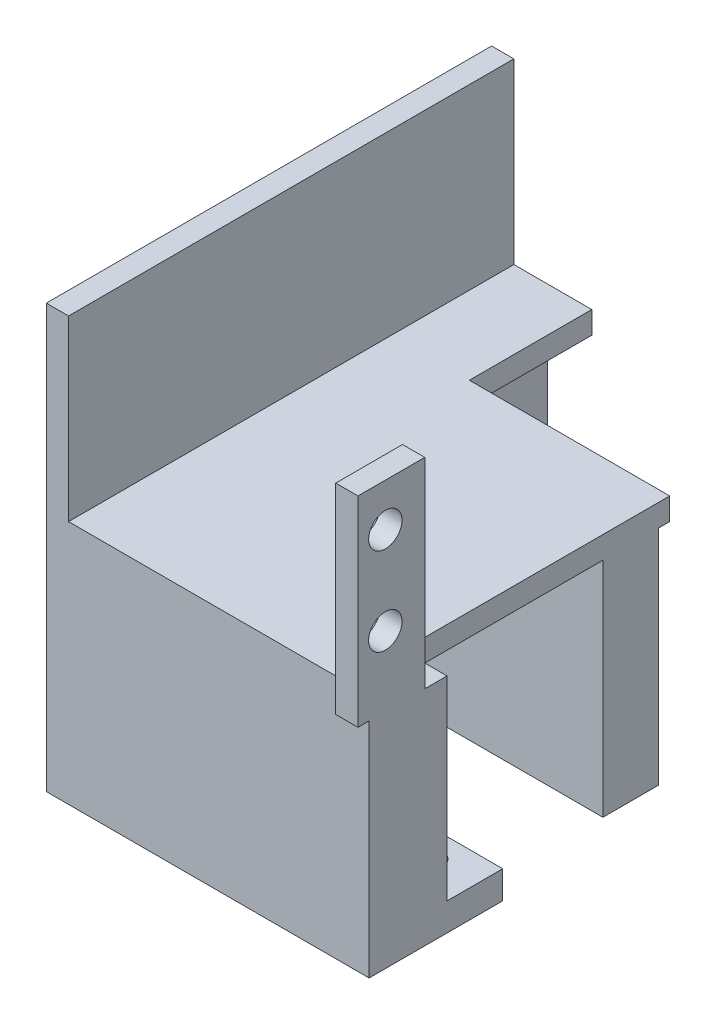
SolidWorks part; units mm, degrees
material "ABS"
ref_plane "Front" through (0, 0, 0) normal (0, 0, 1) x (1, 0, 0)
ref_plane "Top" through (0, 0, 0) normal (0, 1, 0) x (1, 0, 0)
ref_plane "Right" through (0, 0, 0) normal (1, 0, 0) x (0, 0, -1)
sketch "Sketch1" plane through (0, 0, 0) normal (0, 1, 0) x (1, 0, 0)
  line L1 (0, 0) -> (31.75, 0)
  line L2 (0, 0) -> (0, 54.61)
  line L3 (0, 54.61) -> (31.75, 54.61)
  line L4 (31.75, 0) -> (31.75, 54.61)
  dimension "D1" = 31.75
  dimension "D2" = 54.61
extrude "Boss-Extrude1" add sketch "Sketch1" along normal blind 2.54 contours L1 L4 L3 L2
sketch "Sketch2" plane through (0, 0, 0) normal (0, 1, 0) x (1, 0, 0)
  line L0 (31.75, 27.305) -> (-11.8437, 27.305) construction
  line L1 (31.75, -1.27) -> (34.29, -1.27)
  line L2 (31.75, -1.27) -> (31.75, 6.35)
  line L3 (31.75, 6.35) -> (34.29, 6.35)
  line L4 (34.29, -1.27) -> (34.29, 6.35)
  line L6 (31.75, 0) -> (31.75, 54.61) construction
  line L7 (31.75, 48.26) -> (34.29, 48.26)
  line L8 (34.29, 55.88) -> (34.29, 48.26)
  line L9 (31.75, 55.88) -> (34.29, 55.88)
  line L10 (31.75, 55.88) -> (31.75, 48.26)
  line L11 (0, 0) -> (31.75, 0) construction
  line L12 (0, 0) -> (-2.54, 0)
  line L13 (0, 0) -> (0, 54.61)
  line L14 (0, 54.61) -> (-2.54, 54.61)
  line L15 (-2.54, 0) -> (-2.54, 54.61)
  point P8 (31.75, 27.305)
  dimension "D1" = 7.62
  dimension "D2" = 2.54
  dimension "D3" = 2.54
  dimension "D4" = 1.27
extrude "Boss-Extrude2" add sketch "Sketch2" along normal blind 22.86
sketch "Sketch3" plane through (0, 0, 0) normal (0, -1, 0) x (1, 0, 0)
  line L0 (34.29, 1.27) -> (34.29, -6.35) construction
  line L1 (-2.54, 0) -> (34.29, 0)
  line L2 (-2.54, 0) -> (-2.54, -8.89)
  line L3 (-2.54, -8.89) -> (34.29, -8.89)
  line L4 (34.29, 0) -> (34.29, -8.89)
  line L5 (-2.54, -27.305) -> (39.9335, -27.305) construction
  line L8 (31.75, -6.35) -> (31.75, -48.26) construction
  line L9 (-2.54, -45.72) -> (34.29, -45.72)
  line L10 (34.29, -54.61) -> (34.29, -45.72)
  line L11 (-2.54, -54.61) -> (34.29, -54.61)
  line L12 (-2.54, -54.61) -> (-2.54, -45.72)
  point P10 (31.75, -27.305)
  dimension "D1" = 8.89
extrude "Boss-Extrude3" add sketch "Sketch3" along normal blind 25.4
sketch "Sketch4" plane through (34.29, 0, 0) normal (1, 0, 0) x (0, 0, -1)
  line L1 (27.305, -7.6729) -> (27.305, 45.0882) construction
  line L2 (6.35, 2.54) -> (48.26, 2.54) construction
  circle A0 centre (1.85, 17.9678) radius 1.905
  circle A1 centre (1.85, 7.9678) radius 1.905
  circle A2 centre (52.76, 17.9678) radius 1.905
  circle A3 centre (52.76, 7.9678) radius 1.905
  arc A4 (-0.1731, 16.2178) -> (-0.1731, 19.7178) centre (1.85, 17.9678) ccw construction
  arc A5 (0.205, 6.5449) -> (0.205, 9.3907) centre (1.85, 7.9678) ccw construction
  point P11 (27.305, 2.54)
  dimension "D1" = 3.81
  dimension "D2" = 3.81
extrude "Cut-Extrude1" cut sketch "Sketch4" against normal up to surface (2.54 mm away) up to face at (31.75, 8.4667, -52.9167)
sketch "Sketch5" plane through (0, 0, -54.61) normal (0, 0, -1) x (-1, 0, 0)
  line L1 (-34.29, 0) -> (2.54, 0)
  line L2 (-34.29, 0) -> (-34.29, -25.4)
  line L3 (-34.29, -25.4) -> (2.54, -25.4)
  line L4 (2.54, 0) -> (2.54, -25.4)
extrude "Cut-Extrude2" cut sketch "Sketch5" against normal blind 17.78
sketch "Sketch6" plane through (0, 0, 0) normal (0, -1, 0) x (1, 0, 0)
  line L0 (-2.54, -54.61) -> (31.75, -54.61) construction
  line L10 (31.75, -8.89) -> (31.75, -48.26) construction
  line L11 (-2.54, -54.61) -> (3.81, -54.61)
  line L12 (-2.54, -54.61) -> (-2.54, -29.21)
  line L13 (-2.54, -29.21) -> (1.4037, -29.21)
  line L14 (3.81, -54.61) -> (3.81, -35.56)
  line L15 (1.4037, -29.21) -> (31.75, -29.21)
  line L17 (3.81, -35.56) -> (31.75, -35.56)
  line L18 (31.75, -29.21) -> (31.75, -35.56)
  dimension "D1" = 6.35
  dimension "D2" = 19.05
  dimension "D3" = 6.35
extrude "Boss-Extrude4" add sketch "Sketch6" along normal blind 25.4
sketch "Sketch7" plane through (34.29, 0, 0) normal (1, 0, 0) x (0, 0, -1)
  line L0 (48.26, 0) -> (55.88, 0) construction
  line L1 (55.88, 22.86) -> (36.83, 22.86)
  line L2 (55.88, 22.86) -> (55.88, 0)
  line L3 (55.88, 0) -> (36.83, 0)
  line L4 (36.83, 22.86) -> (36.83, 0)
  dimension "D1" = 19.05
extrude "Cut-Extrude3" cut sketch "Sketch7" against normal blind 25.4
sketch "Sketch8" plane through (-2.54, 0, 0) normal (-1, 0, 0) x (0, 0, 1)
  line L0 (-54.61, 22.86) -> (0, 22.86) construction
  line L1 (-54.61, -25.4) -> (-50.8, -25.4)
  line L2 (-54.61, -25.4) -> (-54.61, 22.86)
  line L3 (-54.61, 22.86) -> (-50.8, 22.86)
  line L4 (-50.8, -25.4) -> (-50.8, 22.86)
  dimension "D1" = 3.81
extrude "Cut-Extrude4" cut sketch "Sketch8" against normal blind 25.4
sketch "Sketch9" plane through (0, 0, -8.89) normal (0, 0, -1) x (-1, 0, 0)
  line L1 (-34.29, -25.4) -> (-24.13, -25.4)
  line L2 (-34.29, -25.4) -> (-34.29, -22.225)
  line L3 (-34.29, -22.225) -> (-24.13, -22.225)
  line L4 (-24.13, -25.4) -> (-24.13, -22.225)
  line L5 (2.54, -25.4) -> (-7.62, -25.4)
  line L6 (2.54, -25.4) -> (2.54, -22.225)
  line L7 (2.54, -22.225) -> (-7.62, -22.225)
  line L8 (-7.62, -25.4) -> (-7.62, -22.225)
  dimension "D1" = 3.175
  dimension "D2" = 3.175
  dimension "D3" = 10.16
  dimension "D4" = 10.16
extrude "Boss-Extrude5" add sketch "Sketch9" along normal blind 6.35
sketch "Sketch10" plane through (-2.54, 0, 0) normal (-1, 0, 0) x (0, 0, 1)
  line L1 (-29.21, -25.4) -> (-39.37, -25.4)
  line L2 (-29.21, -25.4) -> (-29.21, -22.225)
  line L3 (-29.21, -22.225) -> (-39.37, -22.225)
  line L4 (-39.37, -25.4) -> (-39.37, -22.225)
  dimension "D1" = 3.175
  dimension "D2" = 10.16
extrude "Boss-Extrude6" add sketch "Sketch10" along normal blind 6.35
sketch "Sketch11" plane through (0, -22.225, 0) normal (0, 1, 0) x (1, 0, 0)
  line L0 (34.29, 15.24) -> (34.29, 8.89) construction
  line L1 (24.13, 15.24) -> (34.29, 15.24) construction
  line L2 (-2.54, 15.24) -> (-2.54, 8.89) construction
  line L3 (-2.54, 15.24) -> (7.62, 15.24) construction
  line L4 (-8.89, 29.21) -> (-8.89, 39.37) construction
  line L5 (-8.89, 29.21) -> (-2.54, 29.21) construction
  circle A0 centre (29.21, 12.065) radius 1.4224
  circle A1 centre (2.54, 12.065) radius 1.4224
  circle A2 centre (-5.715, 34.29) radius 1.4224
  dimension "D1" = 5.08
  dimension "D2" = 3.175
  dimension "D3" = 2.8448
  dimension "D4" = 5.08
  dimension "D5" = 3.175
  dimension "D6" = 3.175
  dimension "D7" = 5.08
extrude "Cut-Extrude5" cut sketch "Sketch11" against normal through all
